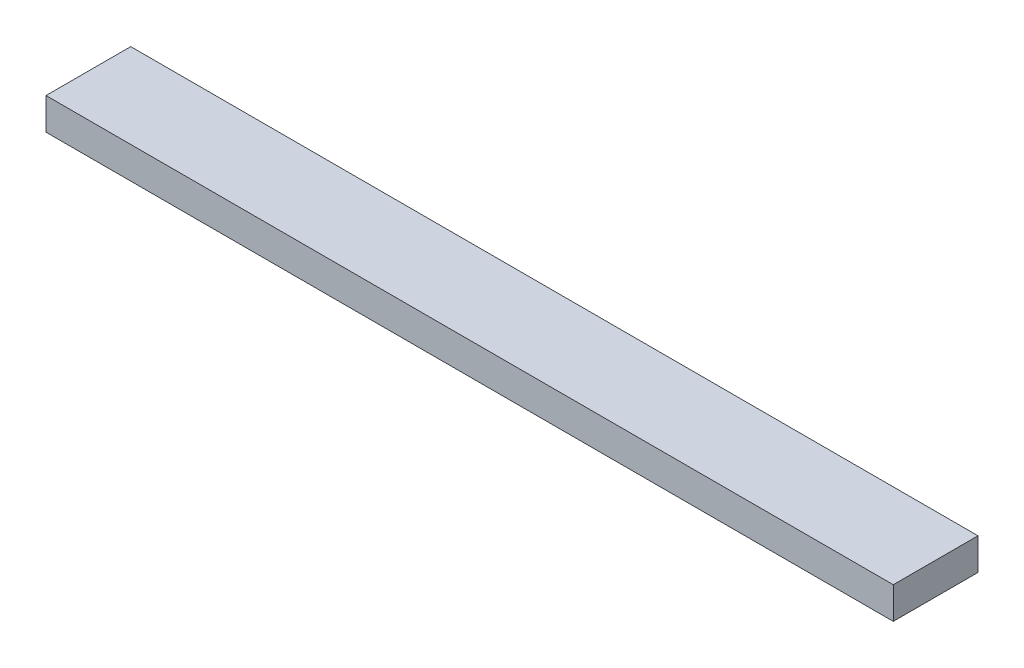
SolidWorks part; units mm, degrees
ref_plane "Front Plane" through (0, 0, 0) normal (0, 0, 1) x (1, 0, 0)
ref_plane "Top Plane" through (0, 0, 0) normal (0, 1, 0) x (1, 0, 0)
ref_plane "Right Plane" through (0, 0, 0) normal (1, 0, 0) x (0, 0, -1)
sketch "Sketch1" plane through (0, 0, 0) normal (0, 1, 0) x (1, 0, 0)
  line L1 (-254, -25.4) -> (254, -25.4)
  line L2 (-254, -25.4) -> (-254, 25.4)
  line L3 (-254, 25.4) -> (254, 25.4)
  line L4 (254, -25.4) -> (254, 25.4)
  line L5 (-254, -25.4) -> (254, 25.4) construction
  line L6 (-254, 25.4) -> (254, -25.4) construction
  point P0 (0, 0)
  dimension "D1" = 508
  dimension "D2" = 50.8
extrude "Boss-Extrude1" add sketch "Sketch1" along normal blind 19.05
